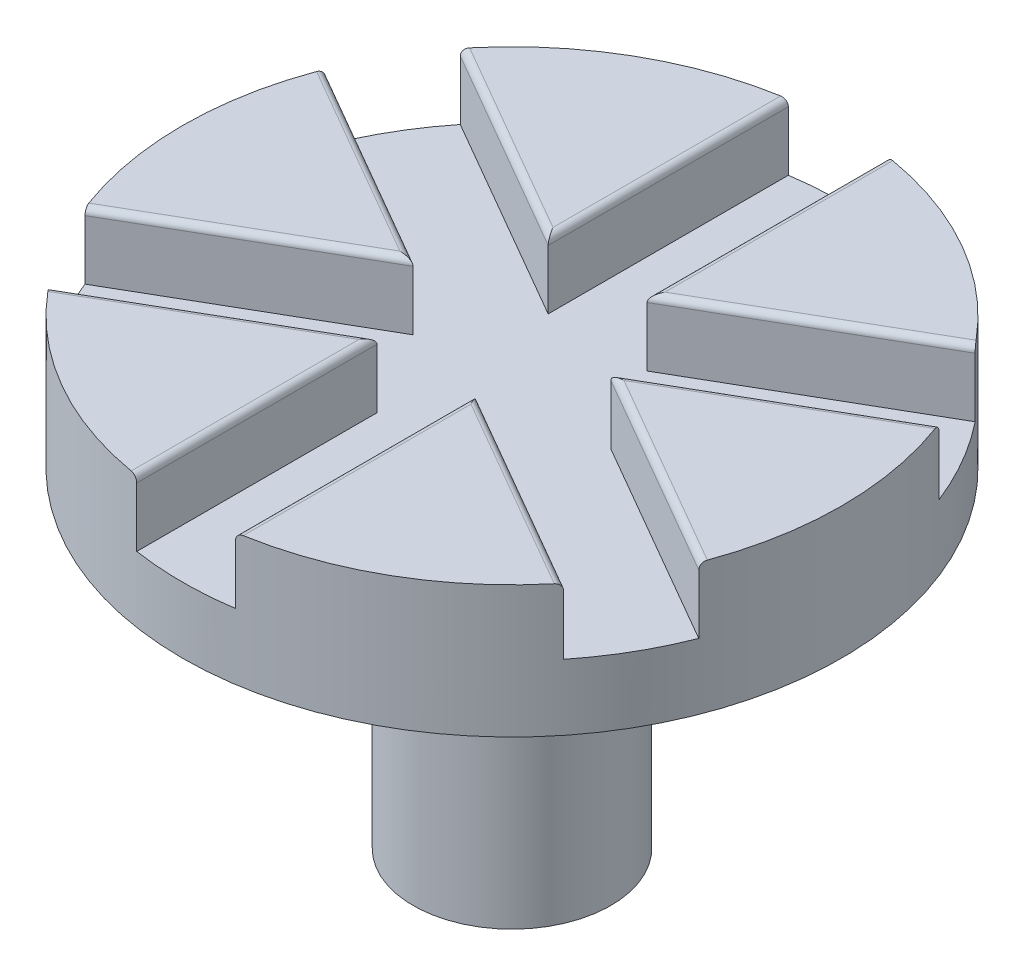
SolidWorks part; units mm, degrees
ref_plane "Front Plane" through (0, 0, 0) normal (0, 0, 1) x (1, 0, 0)
ref_plane "Top Plane" through (0, 0, 0) normal (0, 1, 0) x (1, 0, 0)
ref_plane "Right Plane" through (0, 0, 0) normal (1, 0, 0) x (0, 0, -1)
sketch "Sketch1" plane through (0, 0, 0) normal (0, 1, 0) x (1, 0, 0)
  circle A0 centre (0, 0) radius 127
extrude "Boss-Extrude1" add sketch "Sketch1" along normal blind 25.4
sketch "Sketch2" plane through (0, 25.4, 0) normal (0, 1, 0) x (1, 0, 0)
  line L0 (-19.05, 32.9956) -> (-99.2159, 79.2793)
  line L1 (38.1, 0) -> (19.05, 32.9956)
  line L2 (19.05, 32.9956) -> (-19.05, 32.9956)
  line L3 (-19.05, 32.9956) -> (-38.1, 0)
  line L4 (-38.1, 0) -> (-19.05, -32.9956)
  line L5 (-19.05, -32.9956) -> (19.05, -32.9956)
  line L6 (19.05, -32.9956) -> (38.1, 0)
  line L7 (19.05, 32.9956) -> (19.05, 125.5631)
  line L8 (-19.05, 32.9956) -> (-19.05, 125.5631)
  line L9 (19.05, 32.9956) -> (99.2159, 79.2793)
  line L10 (38.1, 0) -> (118.2659, 46.2838)
  line L11 (38.1, 0) -> (118.2659, -46.2838)
  line L12 (19.05, -32.9956) -> (99.2159, -79.2793)
  line L13 (19.05, -32.9956) -> (19.05, -125.5631)
  line L14 (-19.05, -32.9956) -> (-19.05, -125.5631)
  line L15 (-19.05, -32.9956) -> (-99.1949, -79.3055)
  line L16 (-38.1, 0) -> (-118.2536, -46.315)
  line L17 (-38.1, 0) -> (-118.2659, 46.2838)
  circle A0 centre (0, 0) radius 32.9956 construction
  circle A2 centre (0, 0) radius 127 construction
  circle M7 centre (0, 0) radius 127
  dimension "D1" = 38.1
  dimension "D2" = 38.1
  dimension "D3" = 38.1
  dimension "D4" = 38.1
  dimension "D5" = 38.1
  dimension "D6" = 38.1
extrude "Boss-Extrude2" add sketch "Sketch2" along normal blind 25.4 contours L16 L17 M7 | L0 L8 M7 | L7 L9 M7 | L10 L11 M7 | L12 L13 M7 | L14 L15 M7
sketch "Sketch3" plane through (0, 0, 0) normal (0, -1, 0) x (1, 0, 0)
  circle A0 centre (0, 0) radius 38.1
extrude "Boss-Extrude3" add sketch "Sketch3" along normal blind 127
fillet "Fillet1" radius 2.54 12 edges at (78.1829, 50.8, -23.1419) (59.1329, 50.8, -56.1375) (19.05, 50.8, -79.2793) (78.1829, 50.8, 23.1419) (19.05, 50.8, 79.2793) (59.1329, 50.8, 56.1375) (-59.1225, 50.8, 56.1505) (-19.05, 50.8, 79.2793) (-78.1829, 50.8, -23.1419) (-78.1768, 50.8, 23.1575) (-59.1329, 50.8, -56.1375) (-19.05, 50.8, -79.2793)
